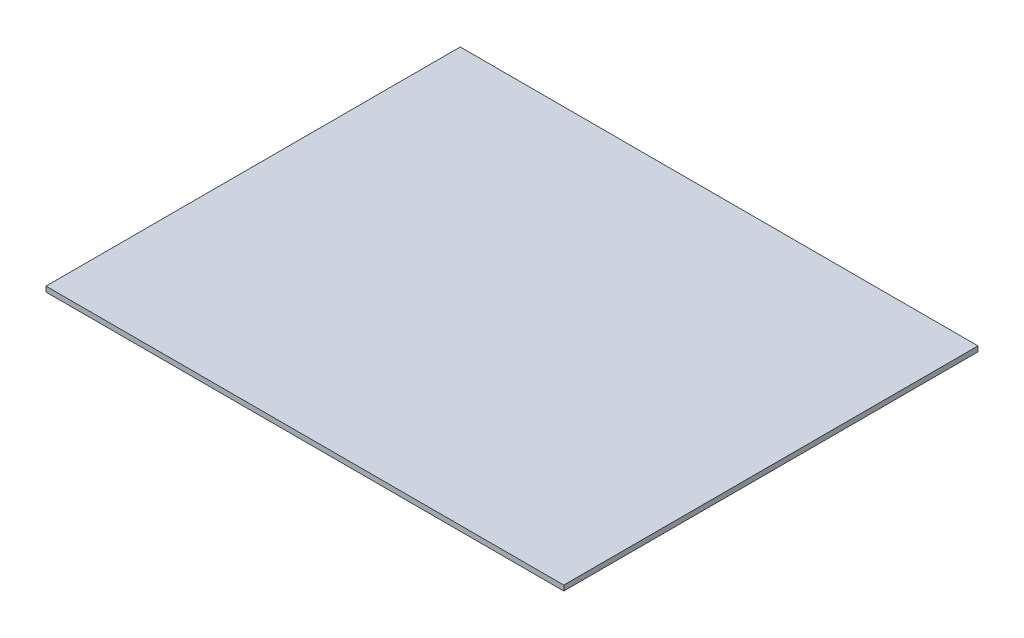
SolidWorks part; units mm, degrees
ref_plane "Front Plane" through (0, 0, 0) normal (0, 0, 1) x (1, 0, 0)
ref_plane "Top Plane" through (0, 0, 0) normal (0, 1, 0) x (1, 0, 0)
ref_plane "Right Plane" through (0, 0, 0) normal (1, 0, 0) x (0, 0, -1)
sketch "Sketch1" plane through (0, 0, 0) normal (0, 1, 0) x (1, 0, 0)
  line L0 (0, -44.7868) -> (0, 44.7868) construction
  line L1 (-250, 200) -> (250, 200)
  line L2 (-250, 200) -> (-250, -200)
  line L3 (-250, -200) -> (250, -200)
  line L4 (250, 200) -> (250, -200)
  line L5 (-44.2539, 0) -> (44.2539, 0) construction
  dimension "D1" = 400
  dimension "D2" = 500
  dimension "D3" = 250
  dimension "D4" = 200
extrude "Boss-Extrude1" add sketch "Sketch1" along normal blind 5
